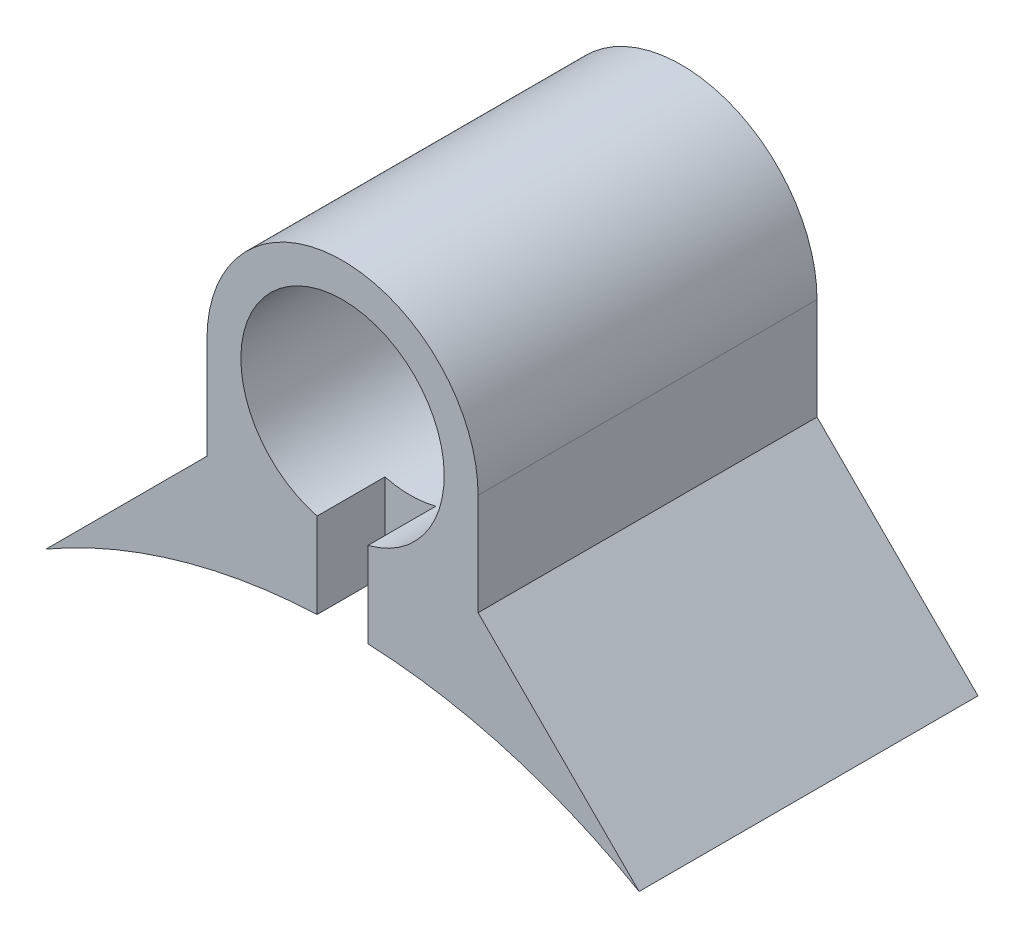
SolidWorks part; units mm, degrees
ref_plane "Front Plane" through (0, 0, 0) normal (0, 0, 1) x (1, 0, 0)
ref_plane "Top Plane" through (0, 0, 0) normal (0, 1, 0) x (1, 0, 0)
ref_plane "Right Plane" through (0, 0, 0) normal (1, 0, 0) x (0, 0, -1)
sketch "Sketch1" plane through (0, 0, 0) normal (0, 0, 1) x (1, 0, 0)
  line L0 (0, 29.0227) -> (0, -32.6134) construction
  line L1 (-48.5491, 0) -> (55.0269, 0) construction
  line L2 (0, 0) -> (8.75, 15.1554) construction
  line L3 (8.75, 15.1554) -> (13.9259, 24.1203) construction
  line L4 (-8.75, 15.1554) -> (-4, 19.9054)
  line L5 (8.75, 15.1554) -> (4, 19.9054)
  line L6 (4, 19.9054) -> (-4, 19.9054)
  line L7 (8.75, 15.1554) -> (-0.4034, 20.4402) construction
  line L8 (4, 22.9054) -> (4, 19.9054)
  line L9 (-4, 22.9054) -> (-4, 19.9054)
  line L10 (-4, 22.9054) -> (4, 22.9054) construction
  arc A0 (-8.75, 15.1554) -> (8.75, 15.1554) centre (0, 0) cw
  circle A1 centre (0, 22.9054) radius 3
  arc A2 (4, 22.9054) -> (-4, 22.9054) centre (0, 22.9054) ccw
  point P8 (0, 17.5)
  point P12 (0, 19.9054)
  dimension "D1" = 17.5
  dimension "D3" = 4
  dimension "D4" = 6
  dimension "D5" = 2.4054
  dimension "D2" = 30
extrude "Boss-Extrude1" add sketch "Sketch1" along normal blind 10 contours L4 A0 L5 L6 | L8 A2 L9 L6 A1
sketch "Sketch3" plane through (0, 0, 10) normal (0, 0, 1) x (1, 0, 0)
  line L0 (0, 27.3657) -> (0, 15.8498) construction
  line L1 (-0.75, 18.7996) -> (0.75, 18.7996)
  line L2 (0.75, 18.7996) -> (0.75, 17.4839)
  line L3 (-0.75, 18.7996) -> (-0.75, 17.4839)
  line L4 (-0.75, 18.7996) -> (-0.75, 20.0007)
  line L5 (0.75, 18.7996) -> (0.75, 20.0007)
  arc A0 (8.75, 15.1554) -> (-8.75, 15.1554) centre (0, 0) ccw construction
  circle A1 centre (0, 22.9054) radius 3 construction
  point P5 (0, 18.7996)
  circle M4 centre (0, 22.9054) radius 3
  arc M6 (-8.75, 15.1554) -> (8.75, 15.1554) centre (0, 0) cw
  dimension "D1" = 1.3157
  dimension "D2" = 1.5
extrude "Cut-Extrude1" cut sketch "Sketch3" against normal blind 2 contours L0 L1 L5 M4 | L0 L4 L1 M4 | L1 L0 L2 M6 | L0 L1 L3 M6
